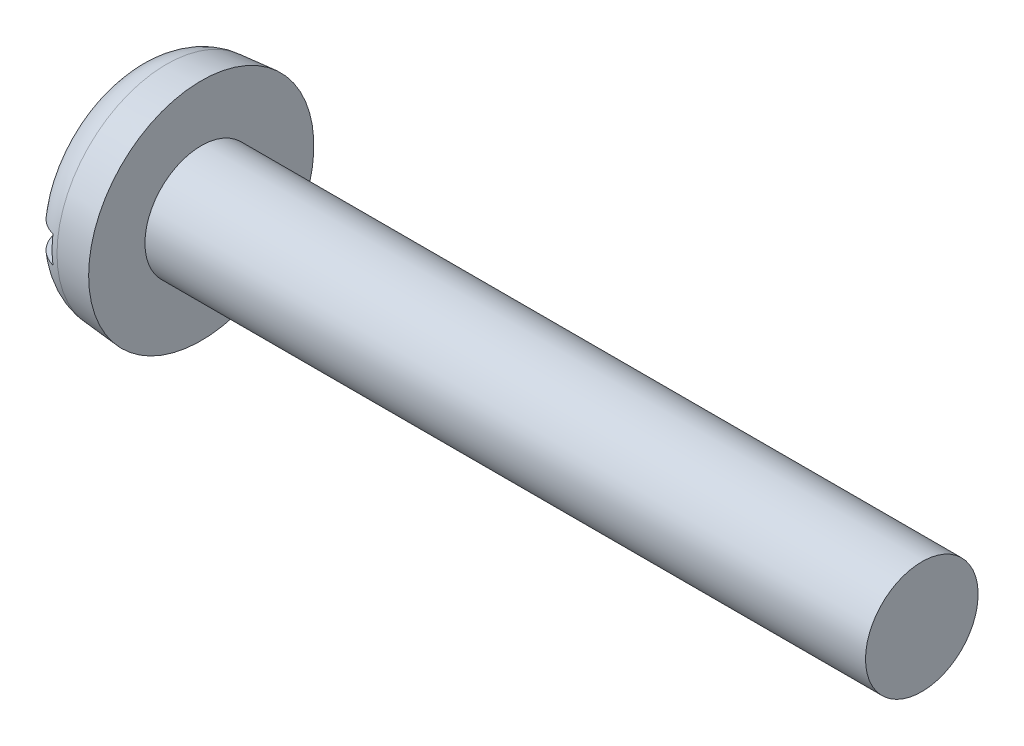
SolidWorks part; units mm, degrees
ref_plane "Plane1" through (0, 0, 0) normal (0, 0, 1) x (1, 0, 0)
ref_plane "Plane2" through (0, 0, 0) normal (0, 1, 0) x (1, 0, 0)
ref_plane "Plane3" through (0, 0, 0) normal (1, 0, 0) x (0, 0, -1)
sketch "BodySke" plane through (0, 0, 0) normal (0, 0, 1) x (1, 0, 0)
  line L0 (1.5, 1.25) -> (1.5, 2.5)
  line L1 (0, 0) -> (0, 2.3688)
  line L2 (-25.4, 0) -> (127, 0) construction
  line L3 (17.5, 0) -> (0, 0)
  line L4 (1.5, 1.25) -> (17.5, 1.25)
  line L5 (17.5, 1.25) -> (17.5, 0)
  line L6 (0, 2.3688) -> (1.5, 2.5)
  line L9 (1.95, 2.8375) -> (1.95, -6.6875) construction
  line L10 (1.5, 6.35) -> (1.5, -3.175) construction
  dimension "Head_ht" = 1.5
  dimension "Diameter" = 2.5
  dimension "Length" = 16
  dimension "Head_dia" = 5
  dimension "Advance" = 0.45
  dimension "Thread_nom" = 16
  dimension "Head_side_angle" = 5
revolve "Base-Revolve" add sketch "BodySke"
cosmetic thread "ThreadCosmetic" [suppressed]
fillet "Fillet1" [suppressed] radius 0.1
fillet "Fillet2" radius 0.8 1 edges at (0, 0, 2.3688)
sketch "Sketch2" plane through (0, 0, 0) normal (1, 0, 0) x (0, 0, -1)
  line L0 (2.5, -0.3) -> (-2.5, -0.3)
  line L1 (2.5, -0.3) -> (2.5, 0.3)
  line L2 (-2.5, 0.3) -> (2.5, 0.3)
  line L3 (-2.5, 0.3) -> (-2.5, -0.3)
  dimension "D1" = 5
  dimension "D2" = 2.5
  dimension "Slot_width" = 0.6
  dimension "D3" = 0.3
extrude "Slot" cut sketch "Sketch2" along normal blind 0.6
sketch "ThdSchSke" plane through (0, 0, 0) normal (0, 0, 1) x (1, 0, 0)
  line L0 (2.4, -0.9965) -> (2.2225, -1.25)
  line L1 (2.4, -0.9965) -> (2.5775, -1.25)
  line L2 (2.5775, -1.25) -> (2.5775, -1.5625)
  line L3 (-3.175, 0) -> (5.1513, 0) construction
  line L5 (2.5775, -1.5625) -> (2.2225, -1.5625)
  line L6 (2.2225, -1.5625) -> (2.2225, -1.25)
  dimension "Thread_minor" = 1.993
  dimension "Diameter" = 2.5
  dimension "Start" = 2.4
  dimension "SideAngle" = 55
  dimension "VeeAngle" = 70
  dimension "Overcut" = 3.125
revolve "ThreadSchematic" [suppressed] cut sketch "ThdSchSke" angle 360 about L3
pattern_linear "ThdSchPat" [suppressed]
equation "\"D1@Sketch2\" = \"Head_dia@BodySke\""
equation "\"D2@Sketch2\" = \"D1@Sketch2\" / 2"
equation "\"D3@Sketch2\" = \"Slot_width@Sketch2\" / 2"
equation "\"Thread_length@ThreadCosmetic\" = ((sgn( (\"Length@BodySke\" - \"Advance@BodySke\" * 2.0 ) - \"Thread_nom@BodySke\" )-1)*( (\"Length@BodySke\" - \"Advance@BodySke\"  * 2.0) - \"Thread_nom@BodySke\" ))/-2+ \"Thread_nom@BodySke\""
equation "\"Thread_minor@ThdSchSke\" = \"Thread_minor@ThreadCosmetic\""
equation "\"Diameter@ThdSchSke\" = \"Diameter@BodySke\""
equation "\"Overcut@ThdSchSke\" = \"Diameter@BodySke\" * 1.25"
equation "\"Start@ThdSchSke\" = \"Head_ht@BodySke\" + \"Length@BodySke\" - \"Thread_length@ThreadCosmetic\"  '---Non-countersunk---"
equation "\"Num_threads@ThdSchPat\" = int( \"Thread_length@ThreadCosmetic\" / \"Advance@BodySke\" + 0.999 )  + 1"
equation "\"Advance@ThdSchPat\" = \"Thread_length@ThreadCosmetic\" /  (\"Num_threads@ThdSchPat\" - 1) 'relax it"
